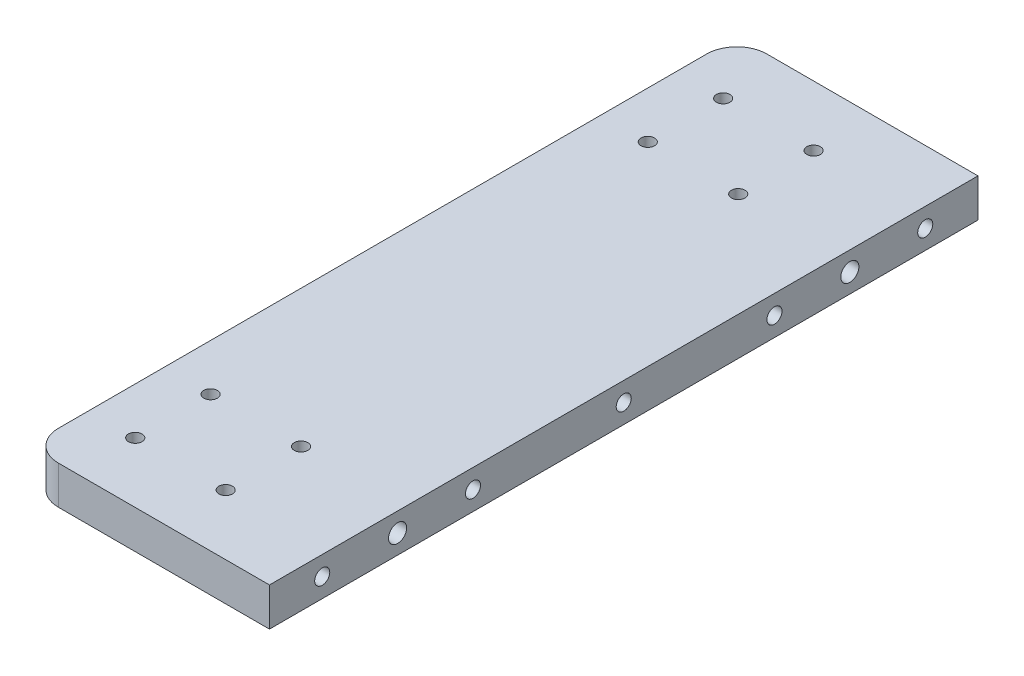
SolidWorks part; units mm, degrees
ref_plane "Front Plane" through (0, 0, 0) normal (0, 0, 1) x (1, 0, 0)
ref_plane "Top Plane" through (0, 0, 0) normal (0, 1, 0) x (1, 0, 0)
ref_plane "Right Plane" through (0, 0, 0) normal (1, 0, 0) x (0, 0, -1)
sketch "Sketch1" plane through (0, 0, 0) normal (0, 1, 0) x (1, 0, 0)
  line L0 (48.3488, 117.5) -> (48.3488, -117.5)
  line L4 (-31.6512, 107.5) -> (-31.6512, -107.5)
  line L5 (48.3488, 117.5) -> (-40.2179, -97.7398) construction
  line L6 (48.3488, -117.5) -> (-40.2179, 97.7398) construction
  line L7 (-21.6512, 117.5) -> (48.3488, 117.5)
  line L8 (-21.6512, -117.5) -> (48.3488, -117.5)
  circle A0 centre (-16.1762, -97.5) radius 2.25
  circle A1 centre (13.8238, -97.5) radius 2.25
  circle A2 centre (13.8238, -72.5) radius 2.25
  circle A3 centre (-16.1762, -72.5) radius 2.25
  circle A4 centre (-16.1762, 72.5) radius 2.25
  circle A5 centre (-16.1762, 97.5) radius 2.25
  circle A6 centre (13.8238, 97.5) radius 2.25
  circle A7 centre (13.8238, 72.5) radius 2.25
  arc A8 (-21.6512, -117.5) -> (-31.6512, -107.5) centre (-21.6512, -107.5) cw
  arc A11 (-21.6512, 117.5) -> (-31.6512, 107.5) centre (-21.6512, 107.5) ccw
  point P0 (0, 0)
  point P5 (-16.1762, -72.5)
  point P6 (13.8238, -72.5)
  point P8 (13.8238, -97.5)
  point P9 (-16.1762, -97.5)
  dimension "D8" = 170
  dimension "D9" = 10
  dimension "D13" = 20
  dimension "D4" = 20
  dimension "D1" = 25
  dimension "D2" = 30
  dimension "D3" = 235
  dimension "D5" = 80
  dimension "D6" = 2
extrude "Boss-Extrude1" add sketch "Sketch1" along normal blind 12.7
sketch "Sketch2" plane through (48.3488, 0, 0) normal (1, 0, 0) x (0, 0, -1)
  line L0 (-117.5, 0) -> (117.5, 0) construction
  line L1 (-117.5, 12.7) -> (-117.5, 0) construction
  point P0 (-100, 6.35)
  point P5 (-50, 6.35)
  point P7 (0, 6.35)
  point P8 (50, 6.35)
  point P9 (100, 6.35)
  dimension "D1" = 6.35
  dimension "D2" = 17.5
  dimension "D4" = 17.5
  dimension "D3" = 5
hole_wizard "Tap Drill for M6x1.0 Tap1" positions "Sketch2" profile "Sketch3" hole size "M6x1.0" standard "ANSI Metric"
sketch "Sketch3" plane through (48.3488, 6.35, 100) normal (0, 1, 0) x (0, 0, -1)
  line L0 (0, 0) -> (0, 18.5022)
  line L1 (0, 18.5022) -> (2.5, 17)
  line L2 (2.5, 17) -> (2.5, 0)
  line L5 (2.5, 0) -> (0, 0)
  line L10 (0, 18.5022) -> (-2.5, 17) construction
  line L11 (0, -6.35) -> (0, 107.95) construction
  dimension "Hole Dia." = 5
  dimension "Hole Depth" = 17
  dimension "Drill Angle" = 118
sketch "Sketch7" plane through (48.3488, 0, 0) normal (1, 0, 0) x (0, 0, -1)
  line L0 (0, 12.7) -> (0, 0) construction
  line L3 (-117.5, 12.7) -> (117.5, 12.7) construction
  line L4 (-117.5, 0) -> (117.5, 0) construction
  point P26 (75, 6.35)
  point P33 (0, 6.35)
  point P34 (-75, 6.35)
  dimension "D1" = 75
  dimension "D2" = 75
hole_wizard "Ø6.0mm Dowel Hole1" positions "Sketch7" profile "Sketch8" hole size "Ø6.0" standard "ANSI Metric"
sketch "Sketch8" plane through (48.3488, 6.35, 75) normal (0, 1, 0) x (0, 0, -1)
  line L0 (0, 0) -> (0, 18.8026)
  line L1 (0, 18.8026) -> (3, 17)
  line L2 (3, 17) -> (3, 0)
  line L5 (3, 0) -> (0, 0)
  line L10 (0, 18.8026) -> (-3, 17) construction
  line L11 (0, -6.35) -> (0, 107.95) construction
  dimension "Hole Dia." = 6
  dimension "Hole Depth" = 17
  dimension "Drill Angle" = 118
